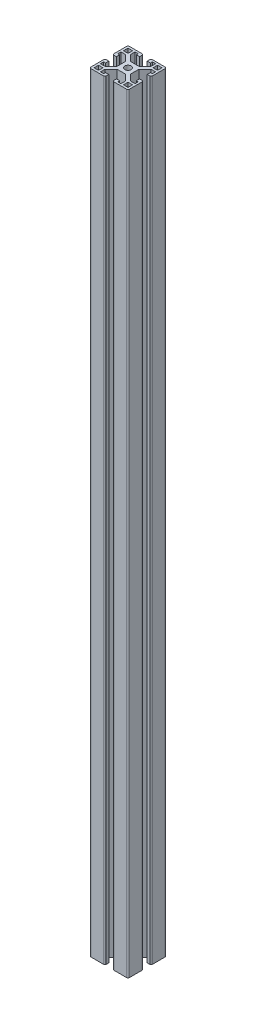
SolidWorks part; units mm, degrees
material "1060 Alloy"
ref_plane "Front Plane" through (0, 0, 0) normal (0, 0, 1) x (1, 0, 0)
ref_plane "Top Plane" through (0, 0, 0) normal (0, 1, 0) x (1, 0, 0)
ref_plane "Right Plane" through (0, 0, 0) normal (1, 0, 0) x (0, 0, -1)
sketch "Sketch1" plane through (0, 0, 0) normal (0, 1, 0) x (1, 0, 0)
  line L0 (-15, 7.5) -> (-15, -4.5)
  line L1 (-15, 7.5) -> (15, 7.5) construction
  line L2 (-15, 7.5) -> (-15, -7.5) construction
  line L3 (-15, -7.5) -> (15, -7.5) construction
  line L4 (15, 7.5) -> (15, -7.5) construction
  line L5 (0, -7.5) -> (0, 7.5) construction
  line L6 (-15, 0) -> (15, 0) construction
  line L7 (-15, 7.5) -> (-3, 7.5)
  line L8 (-15, -4.5) -> (-12, -4.5)
  line L9 (-12, -4.5) -> (-12, -2)
  line L10 (-12, -2) -> (-13.5, -2)
  line L11 (-13.5, -2) -> (-13.5, 0.5)
  line L12 (-13.5, 0.5) -> (-10, 0.5)
  line L13 (-5.25, -2.25) -> (5.25, -2.25) construction
  line L14 (-5.25, -2.25) -> (-5.25, -12.75) construction
  line L15 (-5.25, -12.75) -> (5.25, -12.75) construction
  line L16 (5.25, -2.25) -> (5.25, -12.75) construction
  line L17 (0, -12.75) -> (0, -2.25) construction
  line L18 (-5.25, -7.5) -> (5.25, -7.5) construction
  line L19 (-2.5857, -4.9143) -> (-15, 7.5) construction
  line L20 (-10, 0.5) -> (-5.25, -4.25)
  line L21 (-8, 2.5) -> (-3.25, -2.25)
  line L22 (-3, 7.5) -> (-3, 4.5)
  line L23 (-3, 4.5) -> (-5.5, 4.5)
  line L24 (-5.5, 4.5) -> (-5.5, 6)
  line L25 (-5.5, 6) -> (-8, 6)
  line L26 (-8, 6) -> (-8, 2.5)
  line L27 (5.5, 4.5) -> (5.5, 6)
  line L28 (-13.25, 5.75) -> (-9.75, 5.75)
  line L29 (-13.25, 5.75) -> (-13.25, 2.25)
  line L30 (-13.25, 2.25) -> (-9.75, 2.25)
  line L31 (-9.75, 5.75) -> (-9.75, 2.25)
  line L32 (-11.5, 2.25) -> (-11.5, 5.75) construction
  line L33 (-13.25, 4) -> (-9.75, 4) construction
  line L34 (13.25, 2.25) -> (9.75, 2.25)
  line L35 (13.25, 5.75) -> (13.25, 2.25)
  line L36 (13.25, 5.75) -> (9.75, 5.75)
  line L37 (9.75, 5.75) -> (9.75, 2.25)
  line L38 (3, 4.5) -> (5.5, 4.5)
  line L39 (3, 7.5) -> (3, 4.5)
  line L40 (5.5, 6) -> (8, 6)
  line L41 (8, 6) -> (8, 2.5)
  line L42 (15, 7.5) -> (3, 7.5)
  line L43 (13.5, 0.5) -> (10, 0.5)
  line L44 (13.5, -2) -> (13.5, 0.5)
  line L45 (12, -2) -> (13.5, -2)
  line L46 (15, 7.5) -> (15, -4.5)
  line L47 (15, -4.5) -> (12, -4.5)
  line L48 (12, -4.5) -> (12, -2)
  line L49 (8, 2.5) -> (3.25, -2.25)
  line L50 (10, 0.5) -> (5.25, -4.25)
  line L51 (-5.25, -4.25) -> (-5.25, -10.75)
  line L52 (-3.25, -2.25) -> (3.25, -2.25)
  line L53 (5.25, -4.25) -> (5.25, -10.75)
  line L54 (15, -22.5) -> (15, -10.5)
  line L55 (15, -10.5) -> (12, -10.5)
  line L56 (12, -10.5) -> (12, -13)
  line L57 (12, -13) -> (13.5, -13)
  line L58 (13.5, -13) -> (13.5, -15.5)
  line L59 (13.5, -15.5) -> (10, -15.5)
  line L60 (13.25, -17.25) -> (9.75, -17.25)
  line L61 (13.25, -20.75) -> (13.25, -17.25)
  line L62 (13.25, -20.75) -> (9.75, -20.75)
  line L63 (9.75, -20.75) -> (9.75, -17.25)
  line L64 (8, -21) -> (8, -17.5)
  line L65 (5.5, -21) -> (8, -21)
  line L66 (5.5, -19.5) -> (5.5, -21)
  line L67 (15, -22.5) -> (3, -22.5)
  line L68 (3, -22.5) -> (3, -19.5)
  line L69 (3, -19.5) -> (5.5, -19.5)
  line L70 (10, -15.5) -> (5.25, -10.75)
  line L71 (8, -17.5) -> (3.25, -12.75)
  line L72 (-3, -22.5) -> (-3, -19.5)
  line L73 (-3, -19.5) -> (-5.5, -19.5)
  line L74 (-5.5, -19.5) -> (-5.5, -21)
  line L75 (-5.5, -21) -> (-8, -21)
  line L76 (-8, -21) -> (-8, -17.5)
  line L77 (-15, -22.5) -> (-3, -22.5)
  line L78 (-9.75, -20.75) -> (-9.75, -17.25)
  line L79 (-13.25, -20.75) -> (-9.75, -20.75)
  line L80 (-13.25, -20.75) -> (-13.25, -17.25)
  line L81 (-13.25, -17.25) -> (-9.75, -17.25)
  line L82 (-13.5, -15.5) -> (-10, -15.5)
  line L83 (-13.5, -13) -> (-13.5, -15.5)
  line L84 (-12, -13) -> (-13.5, -13)
  line L85 (-15, -22.5) -> (-15, -10.5)
  line L86 (-15, -10.5) -> (-12, -10.5)
  line L87 (-12, -10.5) -> (-12, -13)
  line L88 (-3.25, -12.75) -> (3.25, -12.75)
  line L89 (-8, -17.5) -> (-3.25, -12.75)
  line L90 (-10, -15.5) -> (-5.25, -10.75)
  circle A0 centre (0, -7.5) radius 2.5
  point P0 (0, 0)
  point P18 (-11.5, 4)
  dimension "D7" = 1.5
  dimension "D19" = 5
  dimension "D1" = 30
  dimension "D2" = 15
  dimension "D3" = 12
  dimension "D4" = 12
  dimension "D5" = 3
  dimension "D6" = 2.5
  dimension "D8" = 2.5
  dimension "D9" = 10.5
  dimension "D10" = 3.5
  dimension "D11" = 45
  dimension "D12" = 3
  dimension "D13" = 2.5
  dimension "D14" = 1.5
  dimension "D15" = 2.5
  dimension "D16" = 3.5
  dimension "D17" = 3.5
  dimension "D18" = 3.5
extrude "Boss-Extrude1" add sketch "Sketch1" against normal blind 600
fillet "Fillet1" radius 1 12 edges at (-3, -300, -7.5) (-15, -300, -7.5) (-15, -300, 4.5) (3, -300, -7.5) (15, -300, -7.5) (15, -300, 4.5) (-15, -300, 10.5) (-15, -300, 22.5) (-3, -300, 22.5) (3, -300, 22.5) (15, -300, 10.5) (15, -300, 22.5)
